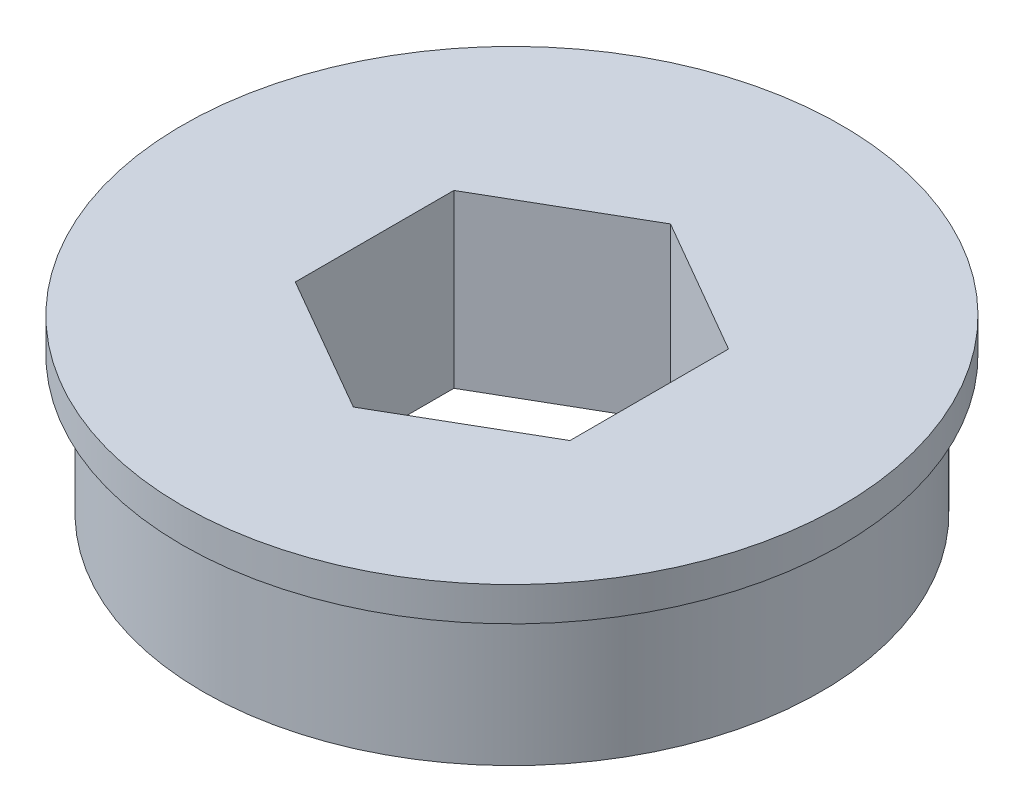
SolidWorks part; units mm, degrees
material "Cast Alloy Steel"
ref_plane "Front Plane" through (0, 0, 0) normal (0, 0, 1) x (1, 0, 0)
ref_plane "Top Plane" through (0, 0, 0) normal (0, 1, 0) x (1, 0, 0)
ref_plane "Right Plane" through (0, 0, 0) normal (1, 0, 0) x (0, 0, -1)
sketch "Sketch1" plane through (0, 0, 0) normal (0, 1, 0) x (1, 0, 0)
  line L1 (0, -7.3323) -> (6.35, -3.6662)
  line L2 (6.35, -3.6662) -> (6.35, 3.6662)
  line L3 (6.35, 3.6662) -> (0, 7.3323)
  line L4 (0, 7.3323) -> (-6.35, 3.6662)
  line L5 (-6.35, 3.6662) -> (-6.35, -3.6662)
  line L6 (-6.35, -3.6662) -> (0, -7.3323)
  circle A0 centre (0, 0) radius 6.35 construction
  circle A1 centre (0, 0) radius 14.2875
extrude "Boss-Extrude1" add sketch "Sketch1" along normal blind 6.35
sketch "Sketch2" plane through (0, 6.35, 0) normal (0, 1, 0) x (1, 0, 0)
  line L1 (0, 7.3323) -> (-6.35, 3.6662)
  line L2 (-6.35, 3.6662) -> (-6.35, -3.6662)
  line L3 (-6.35, -3.6662) -> (0, -7.3323)
  line L4 (0, -7.3323) -> (6.35, -3.6662)
  line L5 (6.35, -3.6662) -> (6.35, 3.6662)
  line L6 (6.35, 3.6662) -> (0, 7.3323)
  circle A0 centre (0, 0) radius 15.24
  circle A1 centre (0, 0) radius 6.35 construction
  dimension "D1" = 30.48
extrude "Boss-Extrude2" add sketch "Sketch2" along normal blind 1.5748
equation "\"D1@Boss-Extrude1\"=0.312-0.062"
